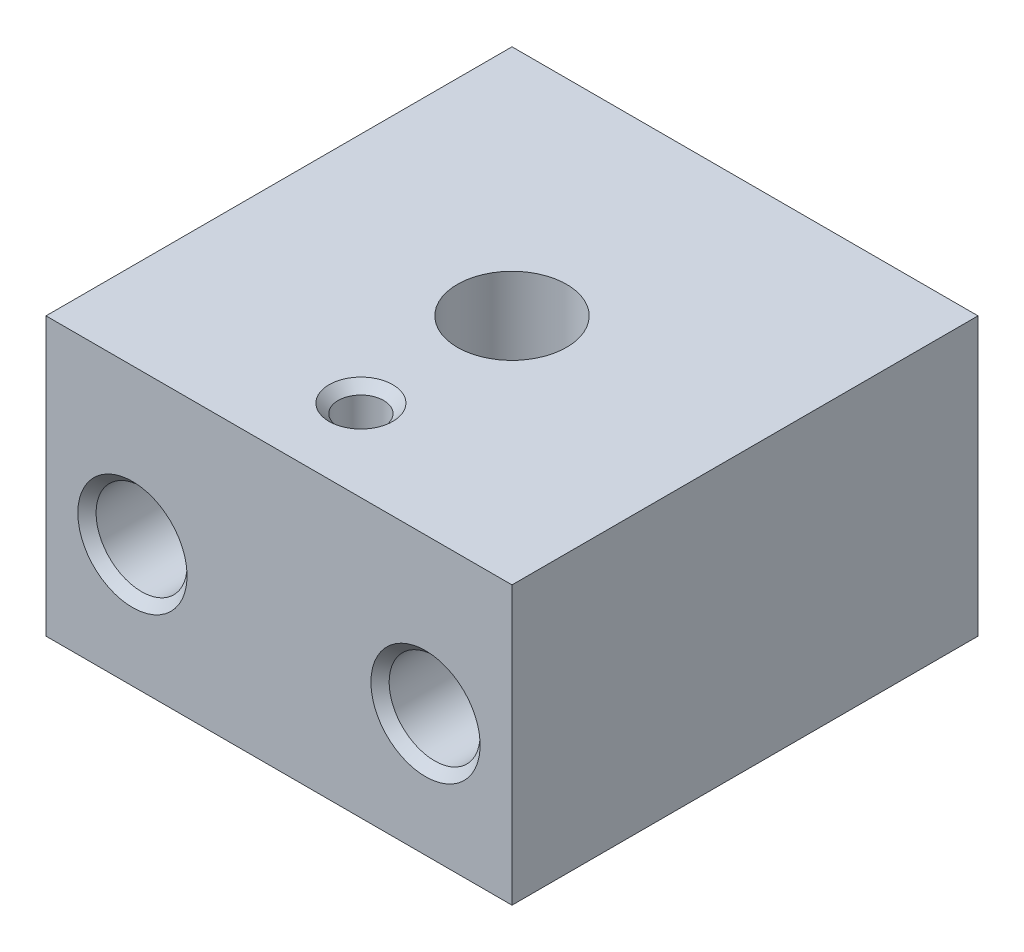
SolidWorks part; units mm, degrees
material "3003 Alloy"
ref_plane "Front Plane" through (0, 0, 0) normal (0, 0, 1) x (1, 0, 0)
ref_plane "Top Plane" through (0, 0, 0) normal (0, 1, 0) x (1, 0, 0)
ref_plane "Right Plane" through (0, 0, 0) normal (1, 0, 0) x (0, 0, -1)
sketch "Sketch1" plane through (0, 0, 0) normal (0, 1, 0) x (1, 0, 0)
  line L1 (-12.8, 12.8) -> (12.8, 12.8)
  line L2 (-12.8, 12.8) -> (-12.8, -12.8)
  line L3 (-12.8, -12.8) -> (12.8, -12.8)
  line L4 (12.8, 12.8) -> (12.8, -12.8)
  point P4 (0, 12.8)
  point P6 (-12.8, 0)
  dimension "D1" = 25.6
  dimension "D2" = 25.6
extrude "Boss-Extrude1" add sketch "Sketch1" along normal blind 15.24
sketch "Sketch2" plane through (0, 0, 12.8) normal (0, 0, 1) x (1, 0, 0)
  line L0 (-12.8, 15.24) -> (-12.8, 0) construction
  line L1 (12.8, 15.24) -> (12.8, 0) construction
  line L2 (-12.8, 15.24) -> (12.8, 15.24) construction
  circle A0 centre (-8.05, 6.74) radius 2.5
  circle A1 centre (8.05, 6.74) radius 2.5
  dimension "D4" = 5
  dimension "D1" = 4.75
  dimension "D2" = 4.75
  dimension "D3" = 8.5
extrude "Cut-Extrude1" cut sketch "Sketch2" against normal through all
sketch "Sketch3" plane through (0, 15.24, 0) normal (0, 1, 0) x (1, 0, 0)
  line L0 (-12.8, -12.8) -> (12.8, -12.8) construction
  circle A0 centre (0, -8.3) radius 1.25
  dimension "D1" = 2.5
  dimension "D2" = 4.5
extrude "Cut-Extrude2" cut sketch "Sketch3" against normal through all
chamfer "Chamfer1" distance 0.5 angle 45 6 edges at (0, 15.24, 9.55) (0, 0, 9.55) (-5.55, 6.74, 12.8) (-5.55, 6.74, -12.8) (10.55, 6.74, 12.8) (10.55, 6.74, -12.8)
sketch "Sketch7" plane through (0, 15.24, 0) normal (0, 1, 0) x (1, 0, 0)
  circle A0 centre (0, 0) radius 3
  dimension "D1" = 6
extrude "Cut-Extrude3" cut sketch "Sketch7" against normal through all
equation "\"D2@Sketch2\" = \"D1@Sketch2\""
